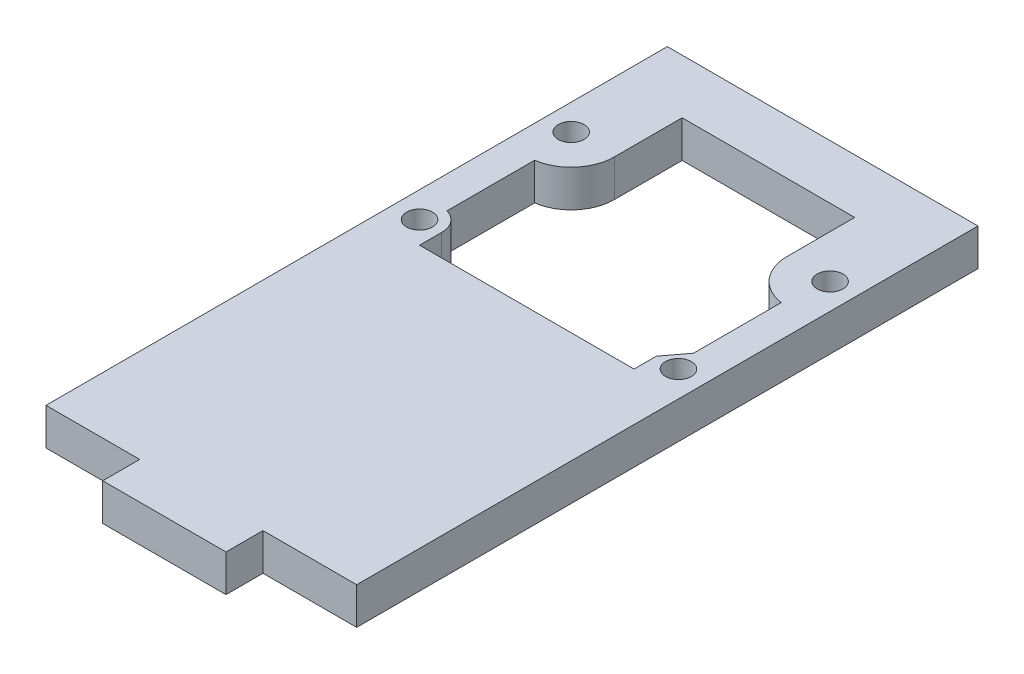
SolidWorks part; units mm, degrees
material "3mm Birch Ply Wood"
ref_plane "Front Plane" through (0, 0, 0) normal (0, 0, 1) x (1, 0, 0)
ref_plane "Top Plane" through (0, 0, 0) normal (0, 1, 0) x (1, 0, 0)
ref_plane "Right Plane" through (0, 0, 0) normal (1, 0, 0) x (0, 0, -1)
sketch "Sketch1" plane through (0, 0, 0) normal (0, 1, 0) x (1, 0, 0)
  line L0 (-12.6, -12) -> (-12.6, -32)
  line L1 (-12.6, 12) -> (12.6, 12)
  line L2 (-12.6, 12) -> (-12.6, -12)
  line L4 (12.6, 12) -> (12.6, -12)
  line L5 (-12.6, -32) -> (-5, -32)
  line L6 (12.6, -32) -> (12.6, -12)
  line L8 (0, -35) -> (-5, -35)
  line L9 (0, -35) -> (5, -35)
  line L10 (-5, -35) -> (-5, -32)
  line L12 (5, -32) -> (5, -35)
  line L13 (5, -32) -> (12.6, -32)
extrude "Boss-Extrude1" add sketch "Sketch1" along normal blind 3
sketch "Sketch2" plane through (0, 0, 0) normal (0, -1, 0) x (1, 0, 0)
  circle A1 centre (10.5, -8.5) radius 1.05
  circle A2 centre (-10.5, -8.5) radius 1.05
  circle A3 centre (-10.5, 3.8) radius 1.05
  circle A4 centre (10.5, 3.8) radius 1.05
extrude "Cut-Extrude1" cut sketch "Sketch2" against normal blind 10
sketch "Sketch5" plane through (0, 0, 0) normal (0, -1, 0) x (-1, 0, 0)
  line L2 (-10, 5.0359) -> (-10, -1.8635)
  line L4 (-8.7, -5.6) -> (8.7, -5.6)
  line L6 (-10, -1.8635) -> (-10, -2.0708)
  line L10 (-8.7, -3.8) -> (-8.7, -5.6)
  line L11 (-10.5, 8.5) -> (-10.5, -3.8) construction
  line L12 (-10.5, 2.35) -> (-6.3593, 2.35) construction
  line L14 (-7, 8.5) -> (-7, 12)
  line L16 (10.5, 2.35) -> (6.3593, 2.35) construction
  line L17 (10.5, 8.5) -> (10.5, -3.8) construction
  line L18 (-12.6, 12) -> (12.6, 12) construction
  line L19 (7, 8.5) -> (7, 12)
  line L20 (7, 12) -> (-7, 12)
  line L21 (8.7, -3.8) -> (8.7, -5.6)
  line L22 (10, -1.8635) -> (10, -2.0708)
  line L23 (10, 5.0359) -> (10, -1.8635)
  line L24 (-10, -2.0708) -> (-8.7, -3.8)
  arc A3 (-10, 5.0359) -> (-7, 8.5) centre (-10.5, 8.5) ccw
  arc A4 (8.7, -3.8) -> (10, -2.0708) centre (10.5, -3.8) cw
  arc A5 (7, 8.5) -> (10, 5.0359) centre (10.5, 8.5) ccw
extrude "Cut-Extrude4" cut sketch "Sketch5" against normal blind 10 contours L2 L6 L24 L10 L4 L21 A4 L22 L23 A5 L19 L20 L14 A3
sketch "Sketch6" plane through (0, 0, 0) normal (0, -1, 0) x (1, 0, 0)
  line L0 (7, -12) -> (7, -14)
  line L1 (7, -14) -> (-7, -14)
  line L2 (-7, -14) -> (-7, -12)
  line L3 (-7, -12) -> (-12.6, -12)
  line L4 (-12.6, -12) -> (-12.6, -18.4)
  line L5 (-12.6, -18.4) -> (12.6, -18.4)
  line L6 (12.6, -18.4) -> (12.6, -12)
  line L42 (7, -12) -> (12.6, -12)
extrude "Boss-Extrude2" add sketch "Sketch6" against normal up to surface (3 mm away) up to face at (10.5, 3, 4.85)
